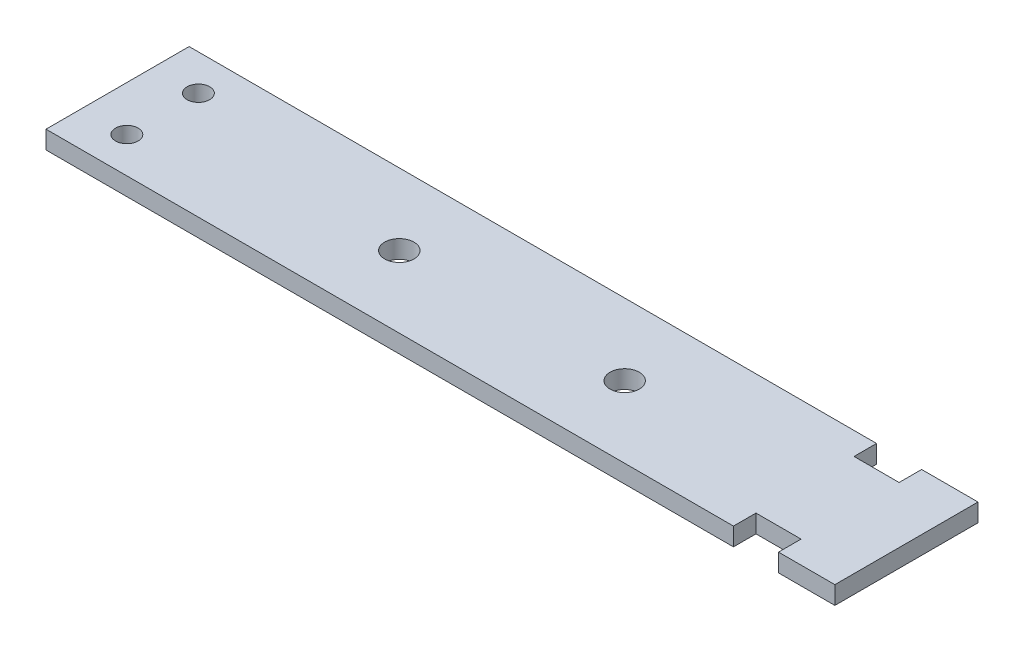
SolidWorks part; units mm, degrees
ref_plane "Front Plane" through (0, 0, 0) normal (0, 0, 1) x (1, 0, 0)
ref_plane "Top Plane" through (0, 0, 0) normal (0, 1, 0) x (1, 0, 0)
ref_plane "Right Plane" through (0, 0, 0) normal (1, 0, 0) x (0, 0, -1)
sketch "Sketch1" plane through (0, 0, 0) normal (0, 1, 0) x (1, 0, 0)
  line L0 (4, 9.525) -> (4, 3.175) construction
  line L1 (0, 0) -> (61, 0)
  line L2 (0, 0) -> (0, 12.7)
  line L3 (0, 12.7) -> (61, 12.7)
  line L4 (70, 0) -> (70, 12.7)
  line L5 (4, 6.35) -> (0, 6.35) construction
  line L6 (65, 12.7) -> (65, 10.7)
  line L7 (65, 10.7) -> (61, 10.7)
  line L8 (61, 10.7) -> (61, 12.7)
  line L9 (61, 0) -> (61, 2)
  line L10 (61, 2) -> (65, 2)
  line L11 (65, 2) -> (65, 0)
  line L12 (65, 12.7) -> (70, 12.7)
  line L13 (65, 0) -> (70, 0)
  circle A0 centre (4, 9.525) radius 1
  circle A1 centre (4, 3.175) radius 1
  circle A2 centre (25, 6.35) radius 1.3
  circle A3 centre (45, 6.35) radius 1.3
  point P17 (39.7463, 9.525)
  point P23 (6.3147, 7.7821)
  dimension "D3" = 2
  dimension "D9" = 2.6
  dimension "D1" = 12.7
  dimension "D2" = 70
  dimension "D4" = 6.35
  dimension "D5" = 4
  dimension "D6" = 5
  dimension "D7" = 4
  dimension "D8" = 2
  dimension "D10" = 20
  dimension "D11" = 25
extrude "Boss-Extrude1" add sketch "Sketch1" along normal blind 1.6
